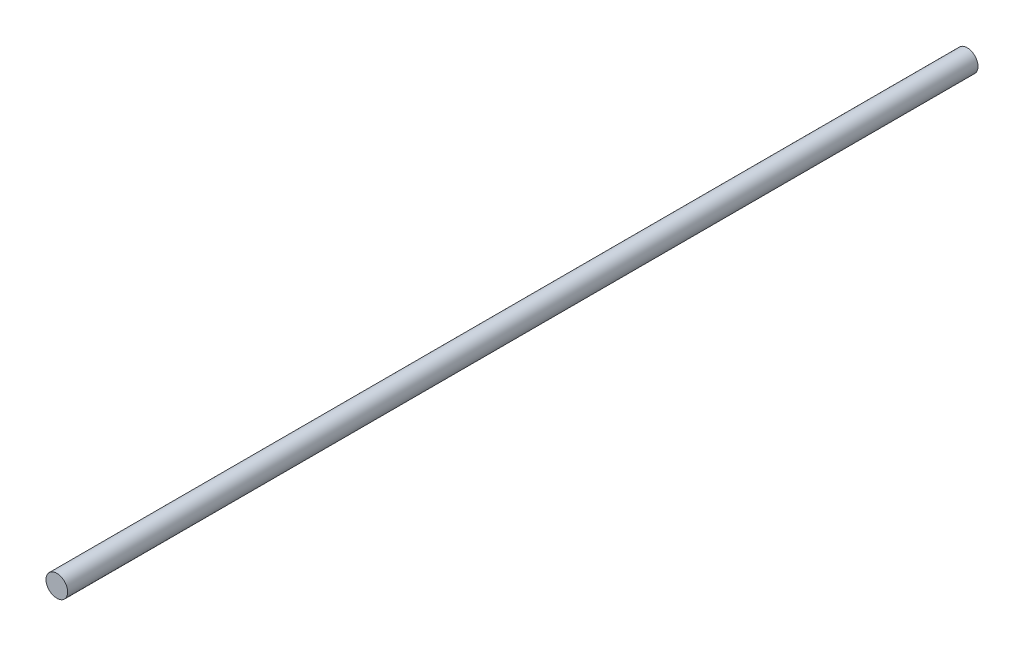
SolidWorks part; units mm, degrees
ref_plane "前视基准面" through (0, 0, 0) normal (0, 0, 1) x (1, 0, 0)
ref_plane "上视基准面" through (0, 0, 0) normal (0, 1, 0) x (1, 0, 0)
ref_plane "右视基准面" through (0, 0, 0) normal (1, 0, 0) x (0, 0, -1)
sketch "草图1" plane through (0, 0, 0) normal (0, 0, 1) x (1, 0, 0)
  circle A0 centre (0, 0) radius 4
  dimension "D1" = 8
extrude "凸台-拉伸1" add sketch "草图1" along normal blind 336
